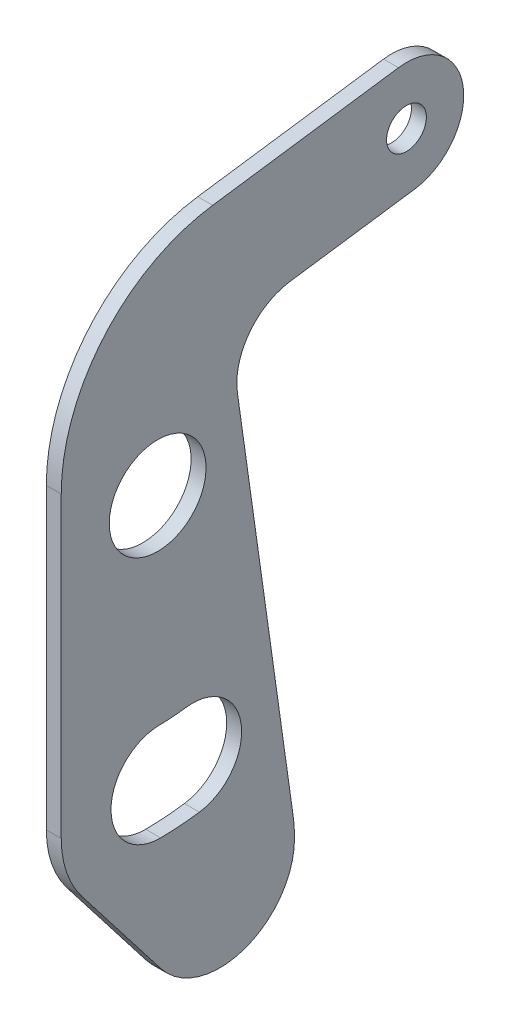
SolidWorks part; units mm, degrees
material "ABS PC"
ref_plane "Front Plane" through (0, 0, 0) normal (0, 0, 1) x (1, 0, 0)
ref_plane "Top Plane" through (0, 0, 0) normal (0, 1, 0) x (1, 0, 0)
ref_plane "Right Plane" through (0, 0, 0) normal (1, 0, 0) x (0, 0, -1)
sketch "Sketch1" plane through (0, 0, 0) normal (1, 0, 0) x (0, 0, -1)
  line L0 (9.525, 0) -> (9.525, -36.83) construction
  line L1 (9.525, -36.83) -> (13.97, -36.83) construction
  line L2 (13.97, -36.83) -> (13.97, -41.91) construction
  line L3 (13.97, -41.91) -> (4.3532, -51.5268) construction
  line L4 (13.8143, -35.1034) -> (7.2541, 11.2869)
  line L7 (9.525, 0) -> (0, 0) construction
  line L8 (0, 0) -> (9.4568, 1.1379) construction
  line L9 (9.4568, 1.1379) -> (13.8568, -35.4283) construction
  line L10 (13.8568, -35.4283) -> (18.2699, -34.8973) construction
  line L11 (18.2699, -34.8973) -> (18.8768, -39.9409) construction
  line L12 (7.2541, 11.2869) -> (26.218, 13.9687)
  line L13 (0, 0) -> (3.5565, -25.1498) construction
  line L14 (24.582, 25.5376) -> (5.6181, 22.8558)
  line L15 (0.325, -41.982) -> (-7.7292, -31.58)
  line L16 (-9.8425, -25.3987) -> (-9.8425, 5.0551)
  circle A0 centre (0, 0) radius 4.7625 construction
  circle A1 centre (0, -25.4) radius 4.7625 construction
  circle A2 centre (0, 0) radius 4.9403
  arc A3 (0.254, -25.3987) -> (3.5565, -25.1498) centre (0, 0) ccw construction
  arc A8 (0.3042, -30.415) -> (4.2589, -30.1169) centre (0, 0) ccw
  arc A9 (0.2038, -20.3825) -> (2.8541, -20.1827) centre (0, 0) ccw
  arc A10 (0.2038, -20.3825) -> (0.3042, -30.415) centre (0.254, -25.3987) ccw
  arc A11 (4.2589, -30.1169) -> (2.8541, -20.1827) centre (3.5565, -25.1498) ccw
  arc A12 (0.325, -41.982) -> (13.97, -37.3169) centre (6.35, -37.3169) ccw
  arc A13 (13.97, -37.3169) -> (13.8143, -35.1034) centre (-1.8381, -37.3169) ccw
  circle A14 centre (25.4, 19.7531) radius 2.032
  arc A15 (26.218, 13.9687) -> (24.582, 25.5376) centre (25.4, 19.7531) ccw
  arc A16 (-9.8425, -25.3987) -> (-7.7292, -31.58) centre (0.254, -25.3987) ccw
  arc A17 (-9.8425, 5.0551) -> (5.6181, 22.8558) centre (8.1353, 5.0551) cw
  point P13 (1.9093, -25.3281)
  dimension "D1" = 9.525
  dimension "D8" = 0.1778
  dimension "D9" = 5.0165
  dimension "D11" = 1.016
  dimension "D12" = 7.62
  dimension "D13" = 8.763
  dimension "D14" = 4.064
  dimension "D15" = 3.81
  dimension "D17" = 5.08
  dimension "D2" = 25.4
  dimension "D3" = 45
  dimension "D4" = 5.08
  dimension "D5" = 13.97
  dimension "D6" = 36.83
  dimension "D7" = 4.445
  dimension "D10" = 10.16
  dimension "D16" = 25.4
extrude "Boss-Extrude1" add sketch "Sketch1" along normal blind 1.524
fillet "Fillet1" radius 6.35 1 edges at (0.762, 11.2869, -7.2541)
sketch "Sketch2" plane through (0, 0, 0) normal (-1, 0, 0) x (0, 0, 1)
  line L15 (57.4449, -41.7413) -> (50.2915, -41.7413)
  line L16 (57.4449, -41.7413) -> (57.4449, -33.1664)
  line L17 (50.2915, -41.7413) -> (50.2915, -33.1664)
  line L18 (57.4449, -33.1664) -> (50.2915, -33.1664)
extrude "Boss-Extrude2" [suppressed] add sketch "Sketch2" against normal up to surface (1.524 mm away)
sketch "Sketch3" [suppressed] plane through (0, 0, 0) normal (-1, 0, 0) x (0, 0, 1)
  line L0 (9.8425, -9.1023) -> (9.8425, -24.3423)
  line L1 (9.8425, -9.1023) -> (33.8673, -9.1023)
  line L2 (9.8425, -24.3423) -> (33.8673, -24.3423)
  line L3 (33.8673, -9.1023) -> (33.8673, -24.3423)
  line L4 (9.8425, 5.0551) -> (9.8425, -25.3987) construction
  line L5 (-21.8041, 25.1447) -> (-6.7142, 23.0108)
  line L6 (-21.8041, 25.1447) -> (-20.6443, 33.3462)
  line L7 (-6.7142, 23.0108) -> (-5.5544, 31.2123)
  line L8 (-20.6443, 33.3462) -> (-5.5544, 31.2123)
  line L9 (-24.582, 25.5376) -> (-5.6181, 22.8558) construction
  dimension "D1" = 15.24
extrude "Boss-Extrude3" [suppressed] add sketch "Sketch3" against normal up to surface (1.524 mm away)
